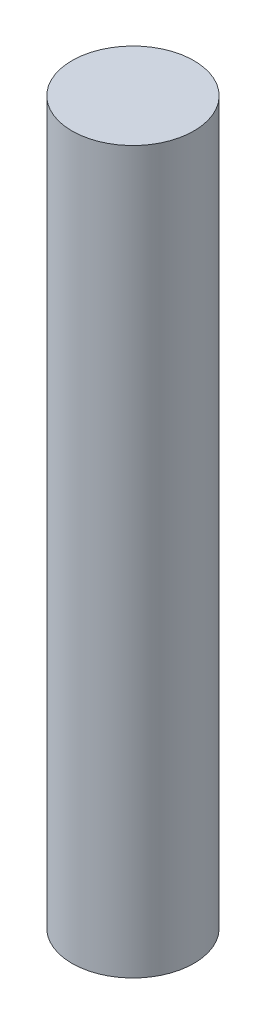
SolidWorks part; units mm, degrees
ref_plane "Front Plane" through (0, 0, 0) normal (0, 0, 1) x (1, 0, 0)
ref_plane "Top Plane" through (0, 0, 0) normal (0, 1, 0) x (1, 0, 0)
ref_plane "Right Plane" through (0, 0, 0) normal (1, 0, 0) x (0, 0, -1)
sketch "Sketch1" plane through (0, 0, 0) normal (0, 1, 0) x (1, 0, 0)
  circle A0 centre (0, 0) radius 6.85
  dimension "D1" = 13.7
extrude "Boss-Extrude1" add sketch "Sketch1" along normal blind 81
